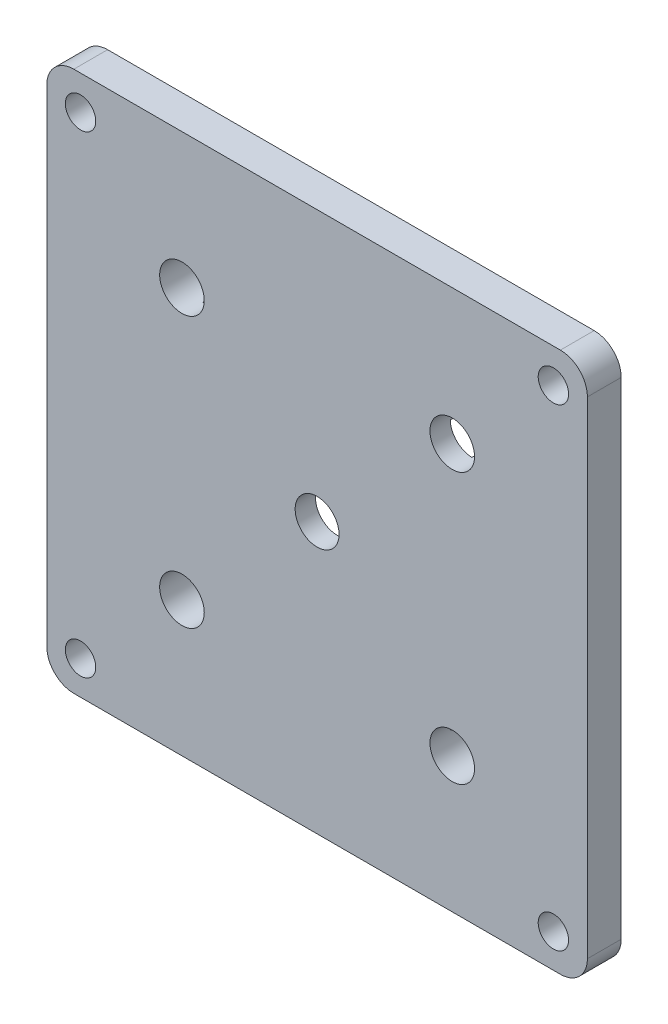
SolidWorks part; units mm, degrees
ref_plane "Plan de face" through (0, 0, 0) normal (0, 0, 1) x (1, 0, 0)
ref_plane "Plan de dessus" through (0, 0, 0) normal (0, 1, 0) x (1, 0, 0)
ref_plane "Plan de droite" through (0, 0, 0) normal (1, 0, 0) x (0, 0, -1)
sketch "Esquisse1" plane through (0, 0, 0) normal (0, 0, 1) x (1, 0, 0)
  line L1 (-36, -40) -> (36, -40)
  line L2 (-40, -36) -> (-40, 36)
  line L3 (-36, 40) -> (36, 40)
  line L4 (40, -36) -> (40, 36)
  line L5 (-40, -40) -> (40, 40) construction
  line L6 (-40, 40) -> (40, -40) construction
  arc A0 (-36, -40) -> (-40, -36) centre (-36, -36) cw
  arc A1 (36, -40) -> (40, -36) centre (36, -36) ccw
  arc A2 (40, 36) -> (36, 40) centre (36, 36) ccw
  arc A3 (-40, 36) -> (-36, 40) centre (-36, 36) cw
  point P0 (0, 0)
  dimension "D3" = 4
  dimension "D1" = 80
  dimension "D2" = 80
extrude "Boss.-Extru.1" add sketch "Esquisse1" along normal blind 5
hole_wizard "Dégagement M41" positions "Esquisse3" profile "Esquisse2" hole size "M4" standard "JIS" end condition through all
sketch "Esquisse3" plane through (0, 0, 5) normal (0, 0, 1) x (1, 0, 0)
  point P0 (-35.0076, 34.9624)
  point P2 (34.9684, 34.9624)
  point P4 (34.9684, -35.0239)
  point P6 (-35.0076, -35.0239)
sketch "Esquisse2" plane through (-35.0076, 34.9624, 5) normal (1, 0, 0) x (0, -1, 0)
  line L0 (0, 0) -> (0, 5)
  line L1 (0, 5) -> (2.25, 5)
  line L2 (2.25, 5) -> (2.25, 0)
  line L5 (2.25, 0) -> (0, 0)
  line L11 (0, -6.35) -> (0, 107.95) construction
  dimension "Diamètre du perçage jusqu'au prochain" = 4.5
  dimension "Profondeur du perçage jusqu'au prochain" = 5
sketch "Esquisse4" plane through (0, 0, 0) normal (0, 0, -1) x (-1, 0, 0)
  circle A0 centre (0, 0) radius 3.25
  dimension "D1" = 6.5
extrude "Enlèv. mat.-Extru.1" cut sketch "Esquisse4" against normal through all
hole_wizard "Dégagement M61" positions "Esquisse6" profile "Esquisse5" hole size "M6" standard "JIS" end condition through all
sketch "Esquisse6" plane through (0, 0, 5) normal (0, 0, 1) x (1, 0, 0)
  point P0 (-20, 20)
  point P2 (20, 20)
  point P4 (20, -20)
  point P6 (-20, -20)
sketch "Esquisse5" plane through (-20, 20, 5) normal (1, 0, 0) x (0, -1, 0)
  line L0 (0, 0) -> (0, 5)
  line L1 (0, 5) -> (3.3, 5)
  line L2 (3.3, 5) -> (3.3, 0)
  line L5 (3.3, 0) -> (0, 0)
  line L11 (0, -6.35) -> (0, 107.95) construction
  dimension "Diamètre du perçage jusqu'au prochain" = 6.6
  dimension "Profondeur du perçage jusqu'au prochain" = 5
sketch "Esquisse7" plane through (0, 0, 0) normal (0, 0, -1) x (-1, 0, 0)
  spline S0 degree 1 poles (-16, 20) (16, 20) knots 0 0 1 1
  spline S1 degree 2 poles (16, 20) (19.6569, 19.6569) (20, 16) knots 0 0 0 1 1 1
  spline S2 degree 1 poles (20, 16) (20, -16) knots 0 0 1 1
  spline S3 degree 2 poles (20, -16) (19.6569, -19.6569) (16, -20) knots 0 0 0 1 1 1
  spline S4 degree 1 poles (16, -20) (-16, -20) knots 0 0 1 1
  spline S5 degree 2 poles (-16, -20) (-19.6569, -19.6569) (-20, -16) knots 0 0 0 1 1 1
  spline S6 degree 1 poles (-20, -16) (-20, 16) knots 0 0 1 1
  spline S7 degree 2 poles (-20, 16) (-19.6569, 19.6569) (-16, 20) knots 0 0 0 1 1 1
extrude "Enlèv. mat.-Extru.2" cut sketch "Esquisse7" against normal blind 2
